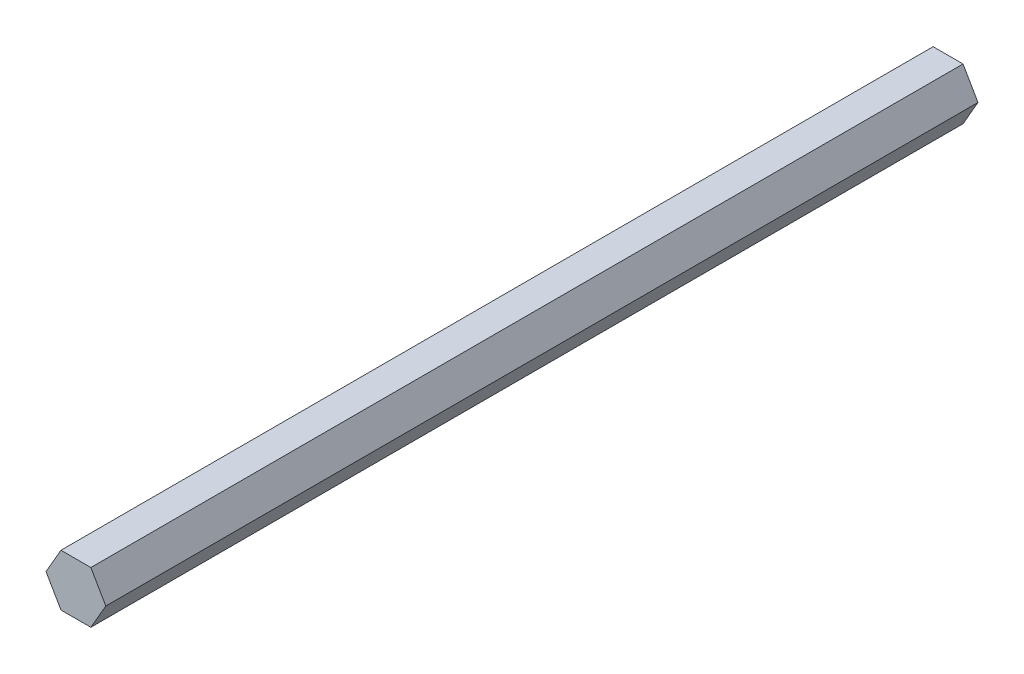
SolidWorks part; units mm, degrees
ref_plane "Front Plane" through (0, 0, 0) normal (0, 0, 1) x (1, 0, 0)
ref_plane "Top Plane" through (0, 0, 0) normal (0, 1, 0) x (1, 0, 0)
ref_plane "Right Plane" through (0, 0, 0) normal (1, 0, 0) x (0, 0, -1)
sketch "Sketch1" plane through (0, 0, 0) normal (0, 0, 1) x (1, 0, 0)
  line L1 (3, 0) -> (1.5, 2.5981)
  line L2 (1.5, 2.5981) -> (-1.5, 2.5981)
  line L3 (-1.5, 2.5981) -> (-3, 0)
  line L4 (-3, 0) -> (-1.5, -2.5981)
  line L5 (-1.5, -2.5981) -> (1.5, -2.5981)
  line L6 (1.5, -2.5981) -> (3, 0)
  circle A0 centre (0, 0) radius 3 construction
  circle A1 centre (0, 0) radius 2.5981 construction
  dimension "D1" = 6
  dimension "D2" = 2.5981
  dimension "D3" = 3
extrude "Boss-Extrude1" add sketch "Sketch1" along normal blind 87.5
